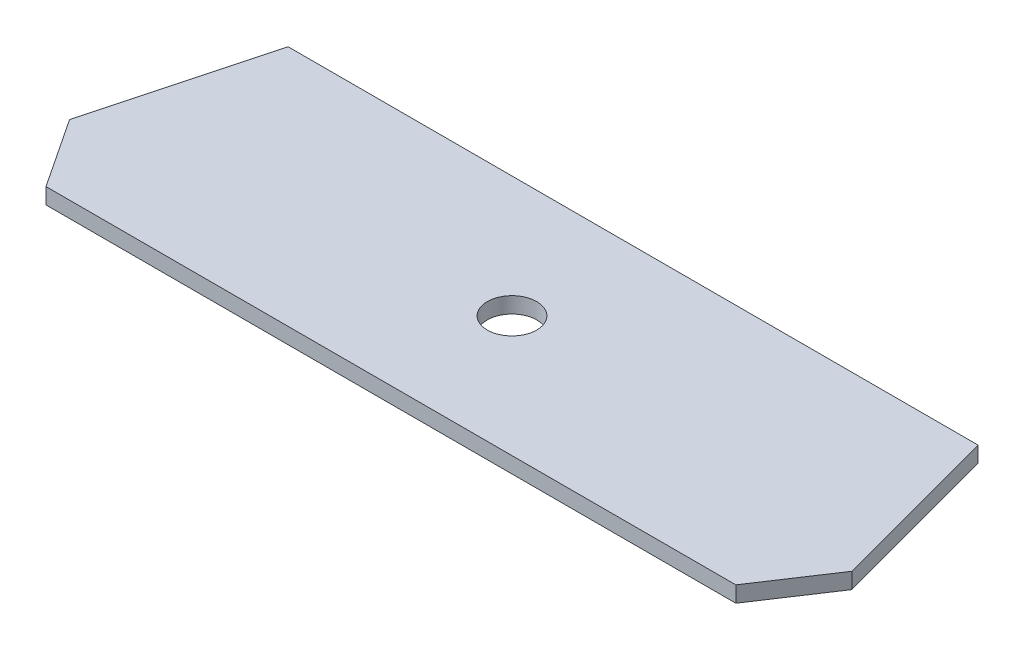
SolidWorks part; units mm, degrees
ref_plane "Front Plane" through (0, 0, 0) normal (0, 0, 1) x (1, 0, 0)
ref_plane "Top Plane" through (0, 0, 0) normal (0, 1, 0) x (1, 0, 0)
ref_plane "Right Plane" through (0, 0, 0) normal (1, 0, 0) x (0, 0, -1)
sketch "Sketch1" plane through (0, 0, 0) normal (0, 1, 0) x (1, 0, 0)
  line L0 (-54.991, 19.304) -> (-62.357, -8.1863)
  line L1 (-54.991, -19.304) -> (54.991, -19.304)
  line L2 (-54.991, -19.304) -> (-54.991, 19.304) construction
  line L3 (-54.991, 19.304) -> (54.991, 19.304)
  line L4 (54.991, -19.304) -> (54.991, 19.304) construction
  line L5 (-54.991, -19.304) -> (54.991, 19.304) construction
  line L6 (-54.991, 19.304) -> (54.991, -19.304) construction
  line L7 (-62.357, -8.1863) -> (-54.991, -19.304)
  line L8 (54.991, -19.304) -> (62.357, -8.1863)
  line L9 (62.357, -8.1863) -> (54.991, 19.304)
  line L10 (-54.991, 19.304) -> (-54.991, -19.304) construction
  point P0 (0, 0)
  dimension "D1" = 38.608
  dimension "D2" = 109.982
  dimension "D3" = 124.714
  dimension "D4" = 15
  dimension "D5" = 15
extrude "Boss-Extrude1" add sketch "Sketch1" along normal blind 2.54
sketch "Sketch2" plane through (0, 2.54, 0) normal (0, 1, 0) x (1, 0, 0)
  circle A0 centre (0, 0) radius 3.937
  dimension "D1" = 7.874
extrude "Cut-Extrude4" cut sketch "Sketch2" against normal up to surface (2.54 mm away) up to face at (0, 0, 2.7288)
